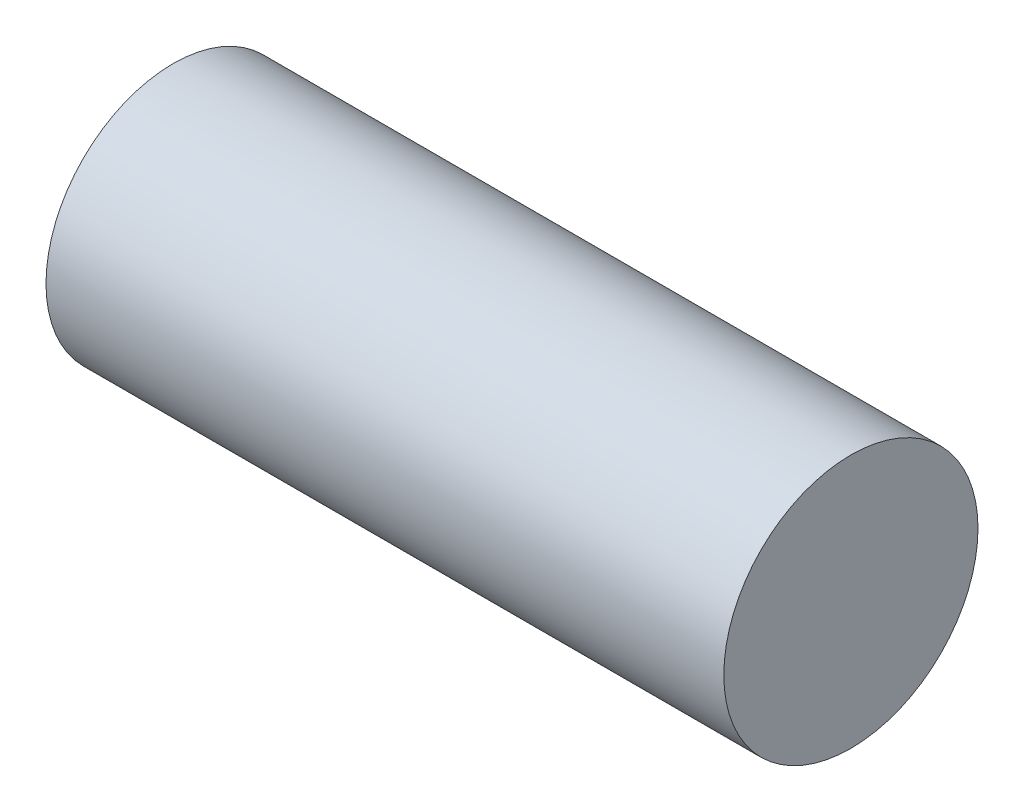
SolidWorks part; units mm, degrees
ref_plane "Front Plane" through (0, 0, 0) normal (0, 0, 1) x (1, 0, 0)
ref_plane "Top Plane" through (0, 0, 0) normal (0, 1, 0) x (1, 0, 0)
ref_plane "Right Plane" through (0, 0, 0) normal (1, 0, 0) x (0, 0, -1)
sketch "Sketch1" plane through (0, 0, 0) normal (1, 0, 0) x (0, 0, -1)
  circle A0 centre (0, 0) radius 7.5
  dimension "D1" = 15
extrude "Boss-Extrude1" add sketch "Sketch1" along normal blind 40
